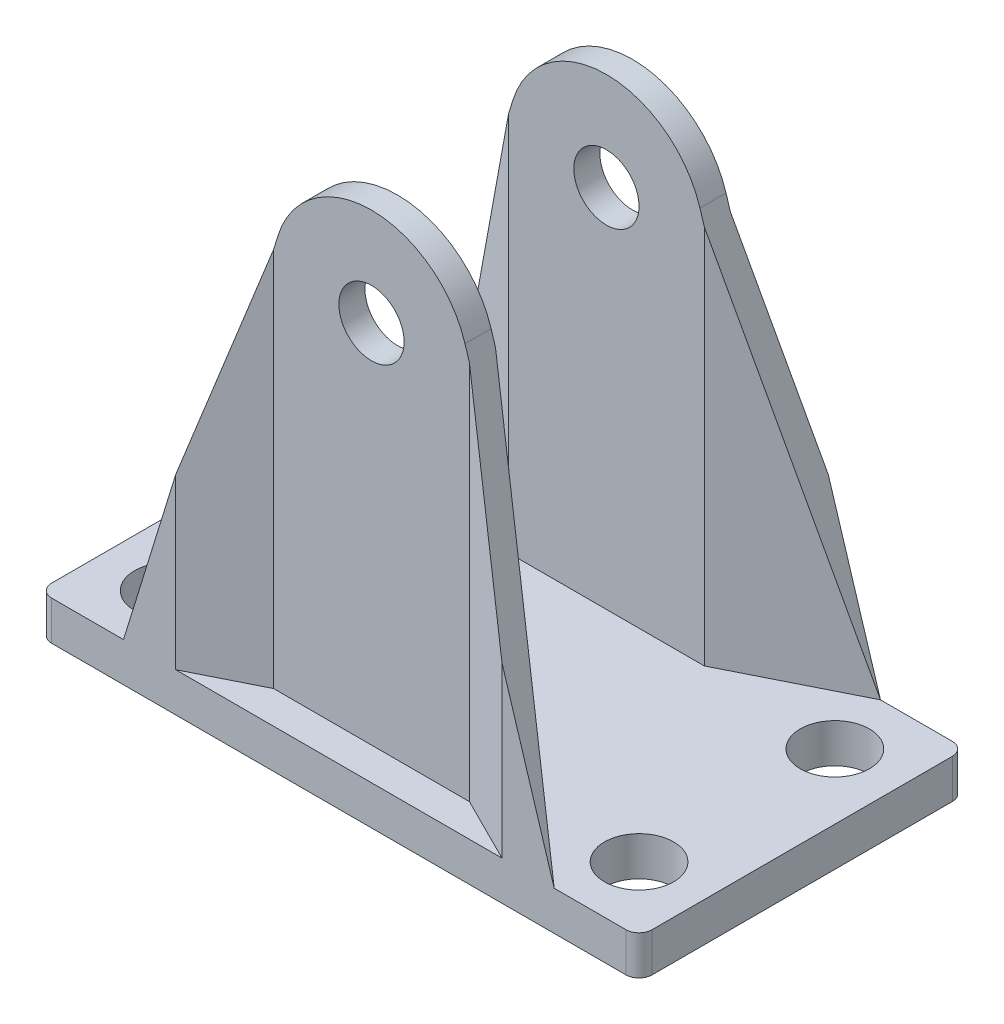
SolidWorks part; units mm, degrees
ref_plane "正面" through (0, 0, 0) normal (0, 0, 1) x (1, 0, 0)
ref_plane "平面" through (0, 0, 0) normal (0, 1, 0) x (1, 0, 0)
ref_plane "右側面" through (0, 0, 0) normal (1, 0, 0) x (0, 0, -1)
sketch "ｽｹｯﾁ1" plane through (0, 0, 0) normal (0, 1, 0) x (1, 0, 0)
  line L1 (-23, -12.5) -> (23, -12.5)
  line L2 (-23, -12.5) -> (-23, 12.5)
  line L3 (-23, 12.5) -> (23, 12.5)
  line L4 (23, -12.5) -> (23, 12.5)
  line L5 (-23, -12.5) -> (23, 12.5) construction
  line L6 (-23, 12.5) -> (23, -12.5) construction
  line L7 (-18, -7.5) -> (18, -7.5) construction
  line L8 (-18, -7.5) -> (-18, 7.5) construction
  line L9 (-18, 7.5) -> (18, 7.5) construction
  line L10 (18, -7.5) -> (18, 7.5) construction
  line L11 (-18, -7.5) -> (18, 7.5) construction
  line L12 (-18, 7.5) -> (18, -7.5) construction
  circle A0 centre (-18, 7.5) radius 2.65
  circle A1 centre (18, 7.5) radius 2.65
  circle A2 centre (-18, -7.5) radius 2.65
  circle A3 centre (18, -7.5) radius 2.65
  point P0 (0, 0)
  point P5 (0, 0)
  dimension "D5" = 5.3
  dimension "D6" = 5.3
  dimension "D7" = 5.3
  dimension "D8" = 5.3
  dimension "D1" = 25
  dimension "D2" = 46
  dimension "D3" = 15
  dimension "D4" = 36
extrude "ﾎﾞｽ - 押し出し1" add sketch "ｽｹｯﾁ1" along normal mid plane 3
fillet "ﾌｨﾚｯﾄ1" radius 1 4 edges at (23, 0, 12.5) (-23, 0, -12.5) (23, 0, -12.5) (-23, 0, 12.5)
sketch "ｽｹｯﾁ2" plane through (0, 1.5, 0) normal (0, 1, 0) x (1, 0, 0)
  line L0 (-7.5, 10) -> (-12.5, 12.5)
  line L1 (-19, -8) -> (19, -8)
  line L2 (-19, -8) -> (-19, 8)
  line L3 (-19, 8) -> (19, 8)
  line L4 (19, -8) -> (19, 8)
  line L5 (-19, -8) -> (19, 8) construction
  line L6 (-19, 8) -> (19, -8) construction
  line L7 (-7.5, 10) -> (7.5, 10)
  line L8 (-7.5, 10) -> (-7.5, 8)
  line L9 (-7.5, 8) -> (7.5, 8)
  line L10 (7.5, 10) -> (7.5, 8)
  line L11 (-7.5, 10) -> (7.5, 8) construction
  line L12 (-7.5, 8) -> (7.5, 10) construction
  line L13 (22, 12.5) -> (-22, 12.5) construction
  line L14 (7.5, 10) -> (12.5, 12.5)
  line L15 (-7.5, 8) -> (-16.5, 12.5)
  line L16 (7.5, 8) -> (16.5, 12.5)
  line L21 (-22, -12.5) -> (22, -12.5)
  line L22 (23, -11.5) -> (23, 11.5)
  line L23 (22, 12.5) -> (-22, 12.5)
  line L24 (-23, 11.5) -> (-23, -11.5)
  line L25 (-22, -12.5) -> (22, -12.5)
  line L26 (23, -11.5) -> (23, 11.5)
  line L27 (22, 12.5) -> (-22, 12.5)
  line L28 (-23, 11.5) -> (-23, -11.5)
  arc A4 (22, -12.5) -> (23, -11.5) centre (22, -11.5) ccw
  arc A5 (23, 11.5) -> (22, 12.5) centre (22, 11.5) ccw
  arc A6 (-22, 12.5) -> (-23, 11.5) centre (-22, 11.5) ccw
  arc A7 (-23, -11.5) -> (-22, -12.5) centre (-22, -11.5) ccw
  arc A8 (22, -12.5) -> (23, -11.5) centre (22, -11.5) ccw
  arc A9 (23, 11.5) -> (22, 12.5) centre (22, 11.5) ccw
  arc A10 (-22, 12.5) -> (-23, 11.5) centre (-22, 11.5) ccw
  arc A11 (-23, -11.5) -> (-22, -12.5) centre (-22, -11.5) ccw
  point P0 (0, 0)
  point P5 (0, 9)
  line M19 (22, 12.5) -> (-22, 12.5)
  dimension "D1" = 16
  dimension "D2" = 38
  dimension "D3" = 2
  dimension "D4" = 15
  dimension "D5" = 5
  dimension "D6" = 5
  dimension "D7" = 0
extrude "ﾎﾞｽ - 押し出し2" add sketch "ｽｹｯﾁ2" along normal blind 50 contours L15 L8 L0 M19 | L10 L7 L8 L3 | L10 L16 L14 M19
mirror "ﾐﾗｰ1" about plane through (0, 0, 0) normal (0, 0, 1) of "ﾎﾞｽ - 押し出し2"
sketch "ｽｹｯﾁ3" plane through (0, 0, 0) normal (0, 0, 1) x (1, 0, 0)
  line L0 (0, -1.5) -> (0, 48.5) construction
  line L1 (-22, -1.5) -> (22, -1.5) construction
  line L2 (0, 48.5) -> (0, 29.5) construction
  line L3 (-12.5, 1.5) -> (-7.5, 1.5) construction
  line L4 (-7.5, 51.5) -> (-12.5, 51.5) construction
  line L5 (-7.5, 1.5) -> (7.5, 1.5) construction
  line L6 (7.5, 51.5) -> (-7.5, 51.5) construction
  line L7 (7.5, 1.5) -> (12.5, 1.5) construction
  line L8 (12.5, 51.5) -> (7.5, 51.5) construction
  line L9 (22, -1.5) -> (22, 1.5) construction
  line L10 (22, 1.5) -> (16.5, 1.5) construction
  line L11 (16.5, 1.5) -> (16.5, 51.5) construction
  line L12 (16.5, 51.5) -> (12.5, 51.5) construction
  line L13 (12.5, 1.5) -> (-12.5, 1.5) construction
  line L14 (-12.5, 51.5) -> (-16.5, 51.5) construction
  line L15 (-16.5, 51.5) -> (-16.5, 1.5) construction
  line L16 (-16.5, 1.5) -> (-22, 1.5) construction
  line L17 (-22, 1.5) -> (-22, -1.5) construction
  line L18 (-12.5, 1.5) -> (-7.5, 1.5)
  line L19 (-7.5, 51.5) -> (-12.5, 51.5)
  line L20 (-7.5, 1.5) -> (7.5, 1.5)
  line L21 (7.5, 51.5) -> (-7.5, 51.5)
  line L22 (7.5, 1.5) -> (12.5, 1.5)
  line L23 (12.5, 51.5) -> (7.5, 51.5)
  line L24 (-22, -1.5) -> (22, -1.5)
  line L25 (22, -1.5) -> (22, 1.5)
  line L26 (22, 1.5) -> (16.5, 1.5)
  line L27 (16.5, 1.5) -> (16.5, 51.5)
  line L28 (16.5, 51.5) -> (12.5, 51.5)
  line L29 (12.5, 1.5) -> (-12.5, 1.5)
  line L30 (-12.5, 51.5) -> (-16.5, 51.5)
  line L31 (-16.5, 51.5) -> (-16.5, 1.5)
  line L32 (-16.5, 1.5) -> (-22, 1.5)
  line L33 (-22, 1.5) -> (-22, -1.5)
  line L34 (-16.5, 1.5) -> (-7.1658, 31.7138)
  line L35 (16.5, 1.5) -> (7.1658, 31.7138)
  line L36 (7.5, 1.5) -> (16.5, 1.5) construction
  line L37 (16.5, 1.5) -> (16.5, 51.5) construction
  line L38 (16.5, 51.5) -> (7.5, 51.5) construction
  line L39 (7.5, 51.5) -> (7.5, 1.5) construction
  line L40 (-16.5, 1.5) -> (-7.5, 1.5) construction
  line L41 (-7.5, 1.5) -> (-7.5, 51.5) construction
  line L42 (-7.5, 51.5) -> (-16.5, 51.5) construction
  line L43 (-16.5, 51.5) -> (-16.5, 1.5) construction
  line L44 (7.5, 1.5) -> (16.5, 1.5)
  line L45 (16.5, 1.5) -> (16.5, 51.5)
  line L46 (16.5, 51.5) -> (7.5, 51.5)
  line L47 (7.5, 51.5) -> (7.5, 1.5)
  line L48 (-16.5, 1.5) -> (-7.5, 1.5)
  line L49 (-7.5, 1.5) -> (-7.5, 51.5)
  line L50 (-7.5, 51.5) -> (-16.5, 51.5)
  line L51 (-16.5, 51.5) -> (-16.5, 1.5)
  circle A0 centre (0, 29.5) radius 7.5
  dimension "D3" = 15
  dimension "D1" = 50
  dimension "D2" = 19
extrude "ｶｯﾄ - 押し出し1" cut sketch "ｽｹｯﾁ3" against normal mid plane 50 contours L23 L47 L35 L27 L28 | A0 L35 L47 L21 L49 L34 | L34 L49 L19 L30 L31
sketch "ｽｹｯﾁ4" plane through (0, 0, -10) normal (0, 0, -1) x (-1, 0, 0)
  circle A0 centre (0, 29.5) radius 2.5
  arc A1 (7.1658, 31.7138) -> (-7.1658, 31.7138) centre (0, 29.5) ccw construction
  dimension "D1" = 5
extrude "ｶｯﾄ - 押し出し2" cut sketch "ｽｹｯﾁ4" against normal mid plane 50
